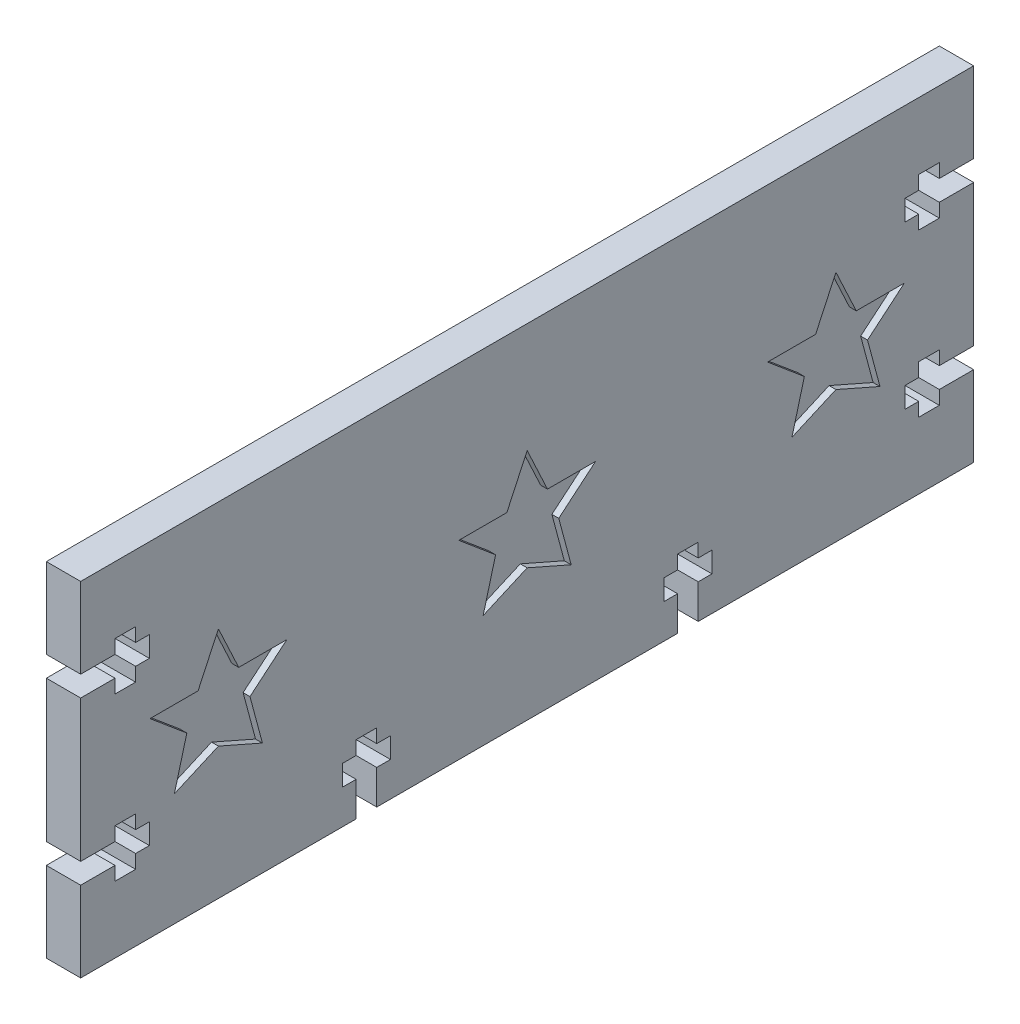
SolidWorks part; units mm, degrees
ref_plane "Front Plane" through (0, 0, 0) normal (0, 0, 1) x (1, 0, 0)
ref_plane "Top Plane" through (0, 0, 0) normal (0, 1, 0) x (1, 0, 0)
ref_plane "Right Plane" through (0, 0, 0) normal (1, 0, 0) x (0, 0, -1)
sketch "Sketch1" plane through (0, 0, 0) normal (1, 0, 0) x (0, 0, -1)
  line L0 (0, -14.859) -> (0, -18.669) construction
  line L1 (0, 0) -> (165.1, 0)
  line L2 (0, 0) -> (0, -14.859)
  line L3 (0, -63.5) -> (165.1, -63.5)
  line L4 (165.1, 0) -> (165.1, -14.859)
  line L5 (0, -18.669) -> (6.35, -18.669)
  line L6 (0, -18.669) -> (0, -14.859) construction
  line L7 (0, -14.859) -> (6.35, -14.859)
  line L8 (12.7, -18.669) -> (12.7, -14.859)
  line L9 (0, -48.641) -> (6.35, -48.641)
  line L10 (0, -48.641) -> (0, -44.831) construction
  line L11 (0, -44.831) -> (6.35, -44.831)
  line L12 (12.7, -48.641) -> (12.7, -44.831)
  line L13 (6.35, -12.319) -> (10.16, -12.319)
  line L14 (6.35, -12.319) -> (6.35, -14.859)
  line L15 (6.35, -21.209) -> (10.16, -21.209)
  line L16 (10.16, -12.319) -> (10.16, -14.859)
  line L17 (6.35, -42.291) -> (10.16, -42.291)
  line L18 (6.35, -42.291) -> (6.35, -44.831)
  line L19 (6.35, -51.181) -> (10.16, -51.181)
  line L20 (10.16, -42.291) -> (10.16, -44.831)
  line L21 (165.1, -14.859) -> (158.75, -14.859)
  line L22 (165.1, -14.859) -> (165.1, -18.669) construction
  line L23 (165.1, -18.669) -> (158.75, -18.669)
  line L24 (152.4, -14.859) -> (152.4, -18.669)
  line L25 (154.94, -12.319) -> (158.75, -12.319)
  line L26 (154.94, -12.319) -> (154.94, -14.859)
  line L27 (154.94, -21.209) -> (158.75, -21.209)
  line L28 (158.75, -12.319) -> (158.75, -14.859)
  line L29 (165.1, -44.831) -> (158.75, -44.831)
  line L30 (165.1, -44.831) -> (165.1, -48.641) construction
  line L31 (165.1, -48.641) -> (158.75, -48.641)
  line L32 (152.4, -44.831) -> (152.4, -48.641)
  line L33 (154.94, -42.291) -> (158.75, -42.291)
  line L34 (154.94, -42.291) -> (154.94, -44.831)
  line L35 (154.94, -51.181) -> (158.75, -51.181)
  line L36 (158.75, -42.291) -> (158.75, -44.831)
  line L37 (0, -18.669) -> (0, -44.831)
  line L38 (6.35, -14.859) -> (6.35, -18.669) construction
  line L39 (6.35, -18.669) -> (6.35, -21.209)
  line L40 (10.16, -14.859) -> (10.16, -18.669) construction
  line L41 (10.16, -18.669) -> (10.16, -21.209)
  line L42 (6.35, -14.859) -> (10.16, -14.859) construction
  line L43 (10.16, -14.859) -> (12.7, -14.859)
  line L44 (6.35, -18.669) -> (10.16, -18.669) construction
  line L45 (10.16, -18.669) -> (12.7, -18.669)
  line L46 (0, -44.831) -> (0, -48.641) construction
  line L47 (0, -48.641) -> (0, -63.5)
  line L48 (6.35, -44.831) -> (6.35, -48.641) construction
  line L49 (6.35, -48.641) -> (6.35, -51.181)
  line L50 (10.16, -44.831) -> (10.16, -48.641) construction
  line L51 (10.16, -48.641) -> (10.16, -51.181)
  line L52 (6.35, -44.831) -> (10.16, -44.831) construction
  line L53 (10.16, -44.831) -> (12.7, -44.831)
  line L54 (6.35, -48.641) -> (10.16, -48.641) construction
  line L55 (10.16, -48.641) -> (12.7, -48.641)
  line L56 (165.1, -44.831) -> (165.1, -48.641) construction
  line L57 (165.1, -48.641) -> (165.1, -63.5)
  line L58 (158.75, -44.831) -> (158.75, -48.641) construction
  line L59 (158.75, -48.641) -> (158.75, -51.181)
  line L60 (154.94, -44.831) -> (154.94, -48.641) construction
  line L61 (154.94, -48.641) -> (154.94, -51.181)
  line L62 (158.75, -44.831) -> (154.94, -44.831) construction
  line L63 (154.94, -44.831) -> (152.4, -44.831)
  line L64 (158.75, -48.641) -> (154.94, -48.641) construction
  line L65 (154.94, -48.641) -> (152.4, -48.641)
  line L66 (165.1, -14.859) -> (165.1, -18.669) construction
  line L67 (165.1, -18.669) -> (165.1, -44.831)
  line L68 (158.75, -14.859) -> (158.75, -18.669) construction
  line L69 (158.75, -18.669) -> (158.75, -21.209)
  line L70 (154.94, -14.859) -> (154.94, -18.669) construction
  line L71 (154.94, -18.669) -> (154.94, -21.209)
  line L72 (158.75, -14.859) -> (154.94, -14.859) construction
  line L73 (154.94, -14.859) -> (152.4, -14.859)
  line L74 (158.75, -18.669) -> (154.94, -18.669) construction
  line L75 (154.94, -18.669) -> (152.4, -18.669)
  point P21 (12.7, -16.764)
  point P22 (12.7, -46.736)
  point P47 (152.4, -46.736)
  point P52 (152.4, -16.764)
  dimension "D1" = 165.1
  dimension "D2" = 63.5
  dimension "D3" = 16.764
  dimension "D4" = 16.764
  dimension "D5" = 12.7
  dimension "D6" = 3.81
  dimension "D7" = 12.7
  dimension "D8" = 3.81
  dimension "D9" = 8.89
  dimension "D10" = 3.81
  dimension "D11" = 2.54
  dimension "D12" = 6.35
  dimension "D13" = 2.54
  dimension "D14" = 6.35
  dimension "D15" = 3.81
  dimension "D16" = 12.7
  dimension "D17" = 3.81
  dimension "D18" = 8.89
  dimension "D19" = 3.81
  dimension "D20" = 2.54
  dimension "D21" = 6.35
  dimension "D22" = 8.89
  dimension "D23" = 16.764
  dimension "D24" = 8.89
  dimension "D25" = 3.81
  dimension "D26" = 3.81
  dimension "D27" = 12.7
  dimension "D28" = 2.54
  dimension "D29" = 6.35
  dimension "D30" = 16.764
extrude "Boss-Extrude1" add sketch "Sketch1" along normal blind 6.35
sketch "Sketch2" plane through (6.35, 0, 0) normal (1, 0, 0) x (0, 0, -1)
  line L0 (0, -63.5) -> (165.1, -63.5) construction
  line L1 (50.927, -63.5) -> (54.737, -63.5)
  line L2 (50.927, -63.5) -> (50.927, -57.15)
  line L3 (50.927, -50.8) -> (54.737, -50.8)
  line L4 (54.737, -63.5) -> (54.737, -57.15)
  line L5 (50.927, -53.34) -> (54.737, -53.34) construction
  line L6 (48.387, -53.34) -> (50.927, -53.34)
  line L7 (48.387, -53.34) -> (48.387, -57.15)
  line L8 (48.387, -57.15) -> (50.927, -57.15)
  line L9 (57.277, -53.34) -> (57.277, -57.15)
  line L10 (110.363, -63.5) -> (114.173, -63.5)
  line L11 (110.363, -63.5) -> (110.363, -57.15)
  line L12 (110.363, -50.8) -> (114.173, -50.8)
  line L13 (114.173, -63.5) -> (114.173, -57.15)
  line L14 (107.823, -53.34) -> (110.363, -53.34)
  line L15 (107.823, -53.34) -> (107.823, -57.15)
  line L16 (107.823, -57.15) -> (110.363, -57.15)
  line L17 (116.713, -53.34) -> (116.713, -57.15)
  line L18 (54.737, -53.34) -> (57.277, -53.34)
  line L19 (50.927, -57.15) -> (54.737, -57.15) construction
  line L20 (54.737, -57.15) -> (57.277, -57.15)
  line L21 (50.927, -57.15) -> (50.927, -53.34) construction
  line L22 (50.927, -53.34) -> (50.927, -50.8)
  line L23 (54.737, -57.15) -> (54.737, -53.34) construction
  line L24 (54.737, -53.34) -> (54.737, -50.8)
  line L25 (110.363, -53.34) -> (114.173, -53.34) construction
  line L26 (114.173, -53.34) -> (116.713, -53.34)
  line L27 (110.363, -57.15) -> (114.173, -57.15) construction
  line L28 (114.173, -57.15) -> (116.713, -57.15)
  line L29 (110.363, -57.15) -> (110.363, -53.34) construction
  line L30 (110.363, -53.34) -> (110.363, -50.8)
  line L31 (114.173, -57.15) -> (114.173, -53.34) construction
  line L32 (114.173, -53.34) -> (114.173, -50.8)
  point P18 (52.832, -50.8)
  point P19 (112.268, -50.8)
  point P20 (82.55, -63.5)
  dimension "D1" = 12.7
  dimension "D2" = 3.81
  dimension "D3" = 3.81
  dimension "D4" = 8.89
  dimension "D5" = 2.54
  dimension "D6" = 6.35
  dimension "D7" = 3.81
  dimension "D8" = 8.89
  dimension "D9" = 3.81
  dimension "D10" = 12.7
  dimension "D11" = 2.54
  dimension "D12" = 6.35
  dimension "D13" = 59.436
  dimension "D14" = 29.718
extrude "Cut-Extrude1" cut sketch "Sketch2" against normal through all
sketch "Sketch3" plane through (6.35, 0, 0) normal (1, 0, 0) x (0, 0, -1)
  line L0 (25.4635, -63.5) -> (25.4635, 0) construction
  line L1 (165.1, 0) -> (0, 0) construction
  line L2 (0, -63.5) -> (50.927, -63.5) construction
  line L3 (82.55, -20.32) -> (78.7929, -28.3771)
  line L4 (139.6365, 0) -> (139.6365, -63.5) construction
  line L5 (114.173, -63.5) -> (165.1, -63.5) construction
  line L6 (78.7929, -28.3771) -> (69.9029, -28.3771)
  line L7 (82.55, -63.5) -> (82.55, 0) construction
  line L8 (54.737, -63.5) -> (110.363, -63.5) construction
  line L9 (25.4635, -20.32) -> (21.7064, -28.3771)
  line L10 (21.7064, -28.3771) -> (12.8164, -28.3771)
  line L11 (12.8164, -28.3771) -> (19.6266, -34.0915)
  line L12 (19.6266, -34.0915) -> (17.3257, -42.6785)
  line L13 (17.3257, -42.6785) -> (25.4635, -39.0998)
  line L14 (25.4635, -39.0998) -> (33.6013, -42.6785)
  line L15 (33.6013, -42.6785) -> (31.3004, -34.0915)
  line L16 (31.3004, -34.0915) -> (38.1106, -28.3771)
  line L17 (38.1106, -28.3771) -> (29.2206, -28.3771)
  line L18 (29.2206, -28.3771) -> (25.4635, -20.32)
  line L19 (69.9029, -28.3771) -> (76.7131, -34.0915)
  line L20 (76.7131, -34.0915) -> (74.4122, -42.6785)
  line L21 (74.4122, -42.6785) -> (82.55, -39.0998)
  line L22 (82.55, -39.0998) -> (90.6878, -42.6785)
  line L23 (90.6878, -42.6785) -> (88.3869, -34.0915)
  line L24 (88.3869, -34.0915) -> (95.1971, -28.3771)
  line L25 (95.1971, -28.3771) -> (86.3071, -28.3771)
  line L26 (86.3071, -28.3771) -> (82.55, -20.32)
  line L27 (139.6365, -20.32) -> (135.8794, -28.3771)
  line L28 (135.8794, -28.3771) -> (126.9894, -28.3771)
  line L29 (126.9894, -28.3771) -> (133.7996, -34.0915)
  line L30 (133.7996, -34.0915) -> (131.4987, -42.6785)
  line L31 (131.4987, -42.6785) -> (139.6365, -39.0998)
  line L32 (139.6365, -39.0998) -> (147.7743, -42.6785)
  line L33 (147.7743, -42.6785) -> (145.4734, -34.0915)
  line L34 (145.4734, -34.0915) -> (152.2836, -28.3771)
  line L35 (152.2836, -28.3771) -> (143.3936, -28.3771)
  line L36 (143.3936, -28.3771) -> (139.6365, -20.32)
  dimension "D1" = 8.89
  dimension "D2" = 8.89
  dimension "D3" = 8.89
  dimension "D4" = 8.89
  dimension "D5" = 8.89
  dimension "D6" = 8.89
  dimension "D7" = 8.89
  dimension "D8" = 40
  dimension "D9" = 115
  dimension "D10" = 8.89
  dimension "D11" = 20.32
  dimension "D12" = 25
  dimension "D13" = 25
  dimension "D14" = 66.262
  dimension "D15" = 66.262
  dimension "D16" = 8.89
  dimension "D17" = 8.89
  dimension "D18" = 8.89
  dimension "D19" = 8.89
  dimension "D20" = 8.89
  dimension "D21" = 8.89
  dimension "D22" = 8.89
  dimension "D23" = 8.89
  dimension "D24" = 8.89
  dimension "D25" = 40
  dimension "D26" = 115
  dimension "D27" = 8.89
  dimension "D28" = 8.89
  dimension "D29" = 8.89
  dimension "D30" = 20.32
  dimension "D31" = 25
  dimension "D32" = 25
  dimension "D33" = 66.262
  dimension "D34" = 66.262
  dimension "D35" = 8.89
  dimension "D36" = 8.89
  dimension "D37" = 8.89
  dimension "D38" = 8.89
  dimension "D39" = 8.89
  dimension "D40" = 8.89
  dimension "D41" = 8.89
  dimension "D42" = 40
  dimension "D43" = 115
  dimension "D44" = 8.89
  dimension "D45" = 20.32
  dimension "D46" = 8.89
  dimension "D47" = 8.89
  dimension "D48" = 25
  dimension "D49" = 25
  dimension "D50" = 66.262
  dimension "D51" = 66.262
extrude "Cut-Extrude2" cut sketch "Sketch3" against normal blind 1.27
